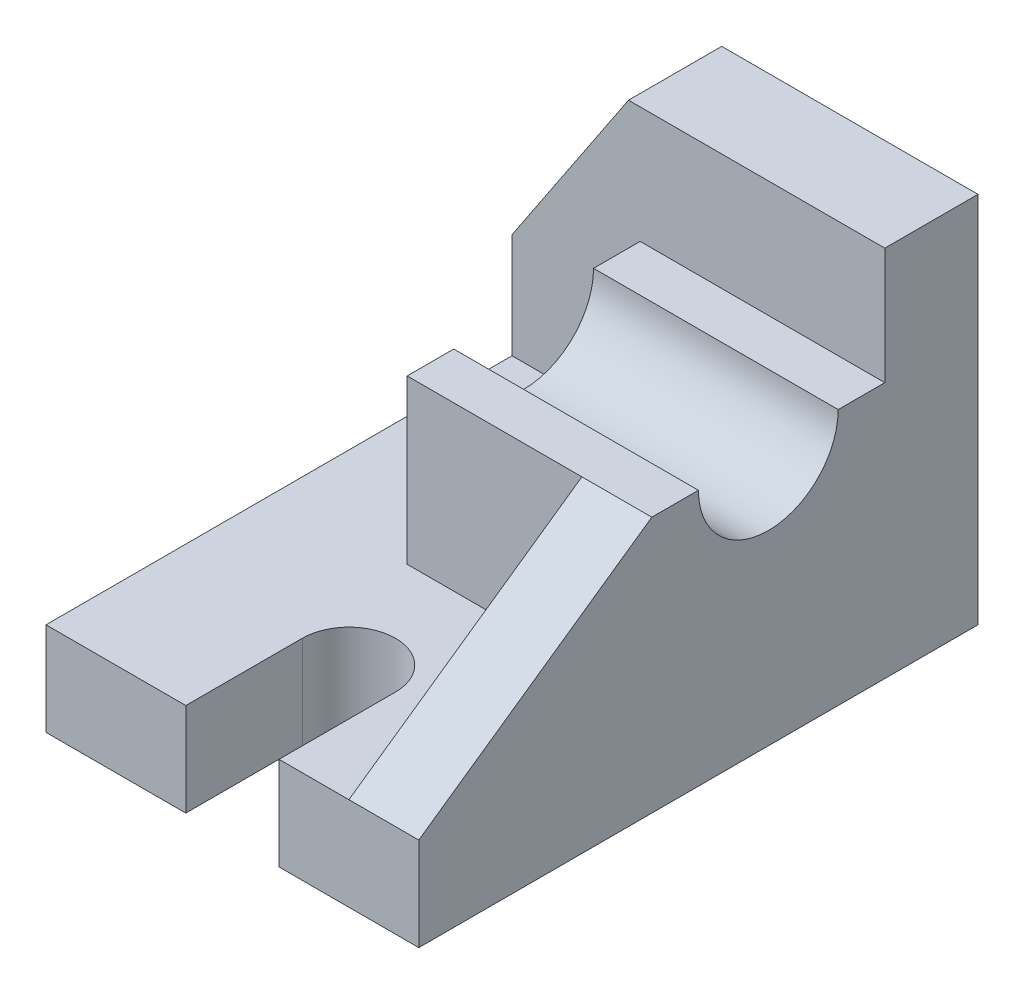
SolidWorks part; units mm, degrees
ref_plane "Ön Düzlem" through (0, 0, 0) normal (0, 0, 1) x (1, 0, 0)
ref_plane "Üst Düzlem" through (0, 0, 0) normal (0, 1, 0) x (1, 0, 0)
ref_plane "Sağ Düzlem" through (0, 0, 0) normal (1, 0, 0) x (0, 0, -1)
sketch "Çizim4" plane through (0, 0, 0) normal (1, 0, 0) x (0, 0, -1)
  line L0 (0, 0) -> (0, 64)
  line L1 (0, 64) -> (-16, 64)
  line L2 (-16, 64) -> (-16, 16)
  line L3 (-16, 16) -> (-96, 16)
  line L4 (0, 0) -> (-96, 0)
  line L5 (-96, 0) -> (-96, 16)
  dimension "D1" = 96
  dimension "D2" = 16
  dimension "D3" = 16
  dimension "D4" = 64
extrude "Yükseklik-Ekstrüzyon1" add sketch "Çizim4" against normal blind 64
sketch "Çizim5" plane through (0, 0, 16) normal (0, 0, 1) x (1, 0, 0)
  line L0 (-64, 64) -> (-44, 64)
  line L1 (-64, 64) -> (0, 64) construction
  line L2 (-44, 64) -> (-64, 34)
  line L3 (-64, 64) -> (-64, 16) construction
  line L4 (-64, 34) -> (-64, 64)
  dimension "D1" = 30
  dimension "D2" = 20
extrude "Kes-Ekstrüzyon1" cut sketch "Çizim5" against normal up to surface (16 mm away) up to face at (-32, 32, 0)
sketch "Çizim6" plane through (0, 16, 0) normal (0, 1, 0) x (1, 0, 0)
  line L0 (-40, -96) -> (-40, -76)
  line L1 (-64, -96) -> (0, -96) construction
  line L2 (-24, -76) -> (-24, -96)
  line L3 (-24, -96) -> (-40, -96)
  line L4 (-64, -16) -> (-64, -96) construction
  arc A0 (-40, -76) -> (-24, -76) centre (-32, -76) cw
  dimension "D1" = 24
  dimension "D2" = 20
  dimension "D3" = 16
extrude "Kes-Ekstrüzyon2" cut sketch "Çizim6" against normal up to surface (16 mm away) up to face at (-32, 0, 48)
sketch "Çizim7" plane through (0, 16, 0) normal (0, 1, 0) x (1, 0, 0)
  line L0 (-64, -16) -> (-64, -96) construction
  line L1 (0, -16) -> (-42, -16)
  line L2 (0, -16) -> (0, -56)
  line L3 (0, -56) -> (-42, -56)
  line L4 (-42, -16) -> (-42, -56)
  dimension "D1" = 22
  dimension "D2" = 40
extrude "Yükseklik-Ekstrüzyon2" add sketch "Çizim7" along normal blind 28
sketch "Çizim9" plane through (0, 0, 0) normal (1, 0, 0) x (0, 0, -1)
  line L0 (-56, 44) -> (-16, 44) construction
  circle A0 centre (-36, 44) radius 12
extrude "Kes-Ekstrüzyon3" cut sketch "Çizim9" against normal up to surface (42 mm away) contours A0 up to face at (-42, 30, 36)
sketch "Çizim10" plane through (0, 0, 0) normal (1, 0, 0) x (0, 0, -1)
  line L0 (-56, 44) -> (-96, 16)
  line L10 (-16, 44) -> (-24, 44)
  line L11 (-48, 44) -> (-56, 44)
  line L12 (-56, 44) -> (-56, 16)
  line L13 (-56, 16) -> (-96, 16)
  line L14 (-96, 16) -> (-96, 0)
  line L15 (-96, 0) -> (0, 0)
  line L16 (0, 0) -> (0, 64)
  line L17 (0, 64) -> (-16, 64)
  line L18 (-16, 64) -> (-16, 44)
  line L21 (-56, 44) -> (-56, 16)
  line L22 (-56, 16) -> (-96, 16)
  arc A1 (-48, 44) -> (-24, 44) centre (-36, 44) ccw
  dimension "D1" = 0
extrude "Yükseklik-Ekstrüzyon3" add sketch "Çizim10" against normal blind 12
